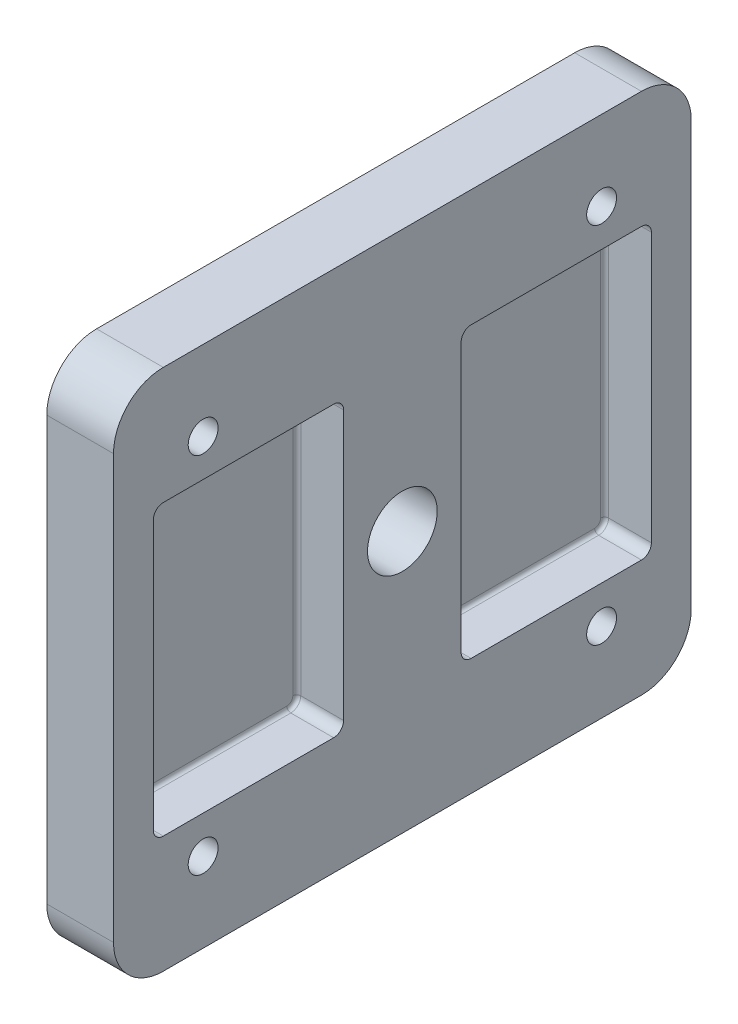
SolidWorks part; units mm, degrees
ref_plane "前视基准面" through (0, 0, 0) normal (0, 0, 1) x (1, 0, 0)
ref_plane "上视基准面" through (0, 0, 0) normal (0, 1, 0) x (1, 0, 0)
ref_plane "右视基准面" through (0, 0, 0) normal (1, 0, 0) x (0, 0, -1)
sketch "草图1" plane through (0, 0, 0) normal (1, 0, 0) x (0, 0, -1)
  line L0 (9, -8) -> (49, -8) construction
  line L1 (5, 0) -> (53, 0)
  line L2 (0, -5) -> (0, -47.5)
  line L3 (5, -52.5) -> (53, -52.5)
  line L4 (58, -5) -> (58, -47.5)
  line L5 (9, -8) -> (9, -44.5) construction
  line L6 (29, -65.5067) -> (29, 26.3628) construction
  line L7 (5, -40.75) -> (22.1, -40.75)
  line L8 (4, -39.75) -> (4, -12.75)
  line L9 (5, -11.75) -> (22.1, -11.75)
  line L10 (23.1, -39.75) -> (23.1, -12.75)
  line L11 (-33.3738, -26.25) -> (92.9545, -26.25) construction
  line L12 (53, -11.75) -> (35.9, -11.75)
  line L13 (34.9, -39.75) -> (34.9, -12.75)
  line L14 (53, -40.75) -> (35.9, -40.75)
  line L15 (54, -39.75) -> (54, -12.75)
  circle A0 centre (9, -8) radius 1.5
  circle A1 centre (49, -8) radius 1.5
  circle A2 centre (49, -44.5) radius 1.5
  circle A3 centre (9, -44.5) radius 1.5
  arc A4 (0, -47.5) -> (5, -52.5) centre (5, -47.5) ccw
  arc A5 (53, -52.5) -> (58, -47.5) centre (53, -47.5) ccw
  arc A6 (53, 0) -> (58, -5) centre (53, -5) cw
  arc A7 (5, 0) -> (0, -5) centre (5, -5) ccw
  arc A8 (34.9, -39.75) -> (35.9, -40.75) centre (35.9, -39.75) ccw
  arc A9 (53, -40.75) -> (54, -39.75) centre (53, -39.75) ccw
  arc A10 (53, -11.75) -> (54, -12.75) centre (53, -12.75) cw
  arc A11 (35.9, -11.75) -> (34.9, -12.75) centre (35.9, -12.75) ccw
  arc A12 (4, -12.75) -> (5, -11.75) centre (5, -12.75) cw
  arc A13 (22.1, -11.75) -> (23.1, -12.75) centre (22.1, -12.75) cw
  arc A14 (22.1, -40.75) -> (23.1, -39.75) centre (22.1, -39.75) ccw
  arc A15 (5, -40.75) -> (4, -39.75) centre (5, -39.75) cw
  point P24 (0, 0)
  point P39 (34.9, -40.75)
  point P42 (54, -40.75)
  point P45 (54, -11.75)
  point P48 (34.9, -11.75)
  point P51 (4, -11.75)
  point P54 (23.1, -11.75)
  point P57 (23.1, -40.75)
  point P60 (4, -40.75)
  dimension "D1" = 3
  dimension "D6" = 8
  dimension "D7" = 9
  dimension "D8" = 8
  dimension "D9" = 9
  dimension "D11" = 5
  dimension "D12" = 19.1
  dimension "D13" = 29
  dimension "D14" = 4
  dimension "D15" = 1
  dimension "D4" = 40
  dimension "D5" = 36.5
  dimension "D10" = 90
  dimension "D2" = 2
  dimension "D3" = 2
extrude "凸台-拉伸1" add sketch "草图1" along normal blind 6.7
sketch "草图2" plane through (0, 0, 0) normal (-1, 0, 0) x (0, 0, 1)
  line L0 (-22.1, -11.75) -> (-5, -11.75) construction
  line L1 (-4, -40.75) -> (-23.1, -40.75)
  line L2 (-4, -40.75) -> (-4, -11.75)
  line L3 (-4, -11.75) -> (-23.1, -11.75)
  line L4 (-23.1, -40.75) -> (-23.1, -11.75)
  line L5 (-5, -40.75) -> (-22.1, -40.75) construction
  line L6 (-4, -12.75) -> (-4, -39.75) construction
  line L7 (-23.1, -39.75) -> (-23.1, -12.75) construction
  line L8 (-29, -63.7029) -> (-29, 9.5688) construction
  line L9 (-58, -47.5) -> (-58, -5) construction
  line L10 (0, -5) -> (0, -47.5) construction
  line L11 (-54, -11.75) -> (-34.9, -11.75)
  line L12 (-34.9, -40.75) -> (-34.9, -11.75)
  line L13 (-54, -40.75) -> (-34.9, -40.75)
  line L14 (-54, -40.75) -> (-54, -11.75)
extrude "凸台-拉伸2" add sketch "草图2" against normal blind 2
sketch "草图3" plane through (6.7, 0, 0) normal (1, 0, 0) x (0, 0, -1)
  line L0 (29, 14.036) -> (29, -71.7541) construction
  line L5 (0, -5) -> (0, -47.5) construction
  line L6 (58, -47.5) -> (58, -5) construction
  line L10 (-11.2118, -26.25) -> (76.3476, -26.25) construction
  line L11 (53, 0) -> (5, 0) construction
  line L12 (5, -52.5) -> (53, -52.5) construction
  circle A4 centre (29, -26.25) radius 3.5
  point P14 (-38.5095, 9.6298)
  dimension "D1" = 7
extrude "切除-拉伸1" cut sketch "草图3" against normal up to next
fillet "圆角1" radius 0.4 16 edges at (2, -12.0429, -35.1929) (2, -26.25, -34.9) (2, -40.4571, -35.1929) (2, -40.75, -44.45) (2, -40.4571, -53.7071) (2, -26.25, -54) (2, -12.0429, -53.7071) (2, -12.0429, -22.8071) (2, -11.75, -13.55) (2, -12.0429, -4.2929) (2, -26.25, -4) (2, -40.4571, -4.2929) (2, -40.75, -13.55) (2, -40.4571, -22.8071) (2, -11.75, -44.45) (2, -26.25, -23.1)
